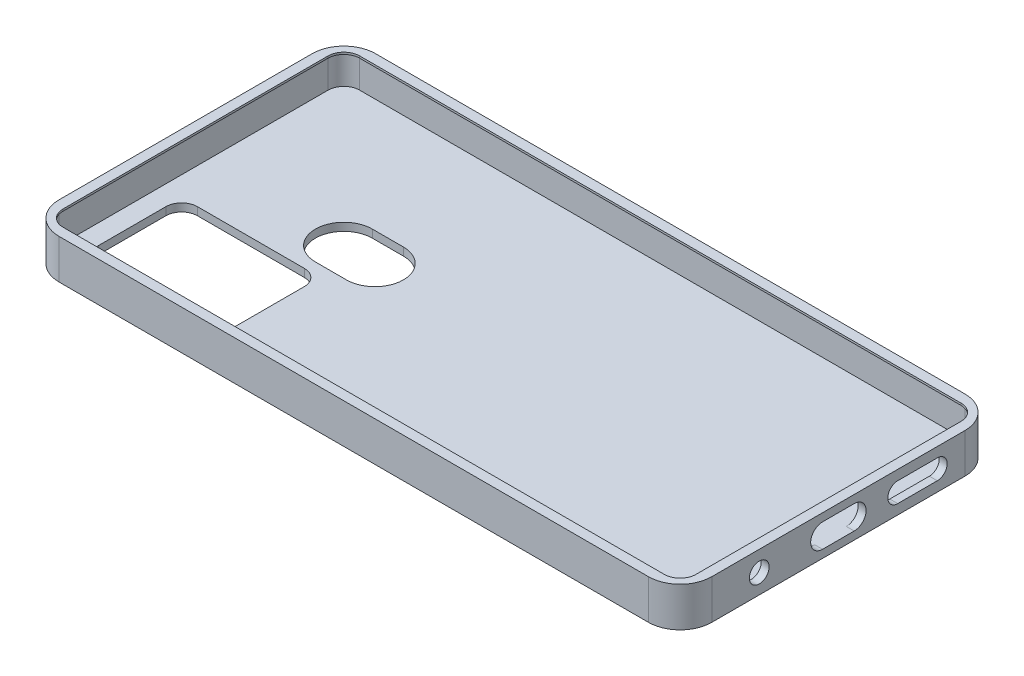
SolidWorks part; units mm, degrees
ref_plane "Front Plane" through (0, 0, 0) normal (0, 0, 1) x (1, 0, 0)
ref_plane "Top Plane" through (0, 0, 0) normal (0, 1, 0) x (1, 0, 0)
ref_plane "Right Plane" through (0, 0, 0) normal (1, 0, 0) x (0, 0, -1)
sketch "Sketch1" plane through (0, 0, 0) normal (0, 1, 0) x (1, 0, 0)
  line L1 (-74.5, 40) -> (74.5, 40)
  line L2 (-82.5, 32) -> (-82.5, -32)
  line L3 (-74.5, -40) -> (74.5, -40)
  line L4 (82.5, 32) -> (82.5, -32)
  arc A0 (74.5, -40) -> (82.5, -32) centre (74.5, -32) ccw
  arc A1 (74.5, 40) -> (82.5, 32) centre (74.5, 32) cw
  arc A2 (-74.5, 40) -> (-82.5, 32) centre (-74.5, 32) ccw
  arc A3 (-82.5, -32) -> (-74.5, -40) centre (-74.5, -32) ccw
  point P7 (82.5, -40)
  point P10 (82.5, 40)
  point P13 (-82.5, 40)
  dimension "D5" = 8
  dimension "D1" = 165
  dimension "D2" = 80
  dimension "D3" = 82.5
  dimension "D4" = 40
extrude "Boss-Extrude1" add sketch "Sketch1" along normal blind 10
sketch "Sketch2" plane through (0, 10, 0) normal (0, 1, 0) x (1, 0, 0)
  line L0 (74.5, 40) -> (-74.5, 40) construction
  line L1 (-76.5, 38) -> (76.5, 38)
  line L2 (-80.5, 34) -> (-80.5, -34)
  line L3 (-76.5, -38) -> (76.5, -38)
  line L4 (80.5, 34) -> (80.5, -34)
  line L5 (-74.5, -40) -> (74.5, -40) construction
  line L6 (82.5, -32) -> (82.5, 32) construction
  line L7 (-82.5, 32) -> (-82.5, -32) construction
  arc A0 (76.5, 38) -> (80.5, 34) centre (76.5, 34) cw
  arc A1 (76.5, -38) -> (80.5, -34) centre (76.5, -34) ccw
  arc A2 (-80.5, -34) -> (-76.5, -38) centre (-76.5, -34) ccw
  arc A3 (-76.5, 38) -> (-80.5, 34) centre (-76.5, 34) ccw
  dimension "D5" = 4
  dimension "D1" = 2
  dimension "D2" = 2
  dimension "D3" = 2
  dimension "D4" = 2
extrude "Cut-Extrude1" cut sketch "Sketch2" against normal blind 8
sketch "Sketch3" plane through (0, 2, 0) normal (0, 1, 0) x (1, 0, 0)
  line L0 (-44.5, 2) -> (-36.6451, 2) construction
  line L1 (-71.5, -8) -> (-44.5, -8)
  line L2 (-75.5, -12) -> (-75.5, -29)
  line L3 (-71.5, -33) -> (-44.5, -33)
  line L4 (-40.5, -12) -> (-40.5, -29)
  line L5 (-76.5, -38) -> (76.5, -38) construction
  line L6 (-80.5, 34) -> (-80.5, -34) construction
  line L7 (-44.5, 9.1985) -> (-36.6451, 9.1985)
  line L8 (-44.5, -5.1985) -> (-36.6451, -5.1985)
  line L9 (-74.5, -40) -> (74.5, -40) construction
  arc A0 (-71.5, -8) -> (-75.5, -12) centre (-71.5, -12) ccw
  arc A1 (-44.5, -8) -> (-40.5, -12) centre (-44.5, -12) cw
  arc A2 (-44.5, -33) -> (-40.5, -29) centre (-44.5, -29) ccw
  arc A3 (-75.5, -29) -> (-71.5, -33) centre (-71.5, -29) ccw
  arc A4 (-44.5, 9.1985) -> (-44.5, -5.1985) centre (-44.5, 2) ccw
  arc A5 (-36.6451, -5.1985) -> (-36.6451, 9.1985) centre (-36.6451, 2) ccw
  point P10 (-75.5, -8)
  point P13 (-40.5, -8)
  point P16 (-40.5, -33)
  point P21 (-40.5726, 2)
  point P26 (0, 0)
  dimension "D5" = 4
  dimension "D1" = 35
  dimension "D2" = 25
  dimension "D3" = 5
  dimension "D4" = 5
  dimension "D6" = 42
extrude "Cut-Extrude2" cut sketch "Sketch3" against normal blind 8
sketch "Sketch4" plane through (82.5, 0, 0) normal (1, 0, 0) x (0, 0, -1)
  line L0 (-4, 5) -> (4, 5) construction
  line L1 (-4, 8) -> (4, 8)
  line L2 (-4, 2) -> (4, 2)
  line L3 (15, 5) -> (25, 5) construction
  line L4 (15, 7.5) -> (25, 7.5)
  line L5 (15, 2.5) -> (25, 2.5)
  arc A0 (-4, 8) -> (-4, 2) centre (-4, 5) ccw
  arc A1 (4, 2) -> (4, 8) centre (4, 5) ccw
  arc A2 (15, 7.5) -> (15, 2.5) centre (15, 5) ccw
  arc A3 (25, 2.5) -> (25, 7.5) centre (25, 5) ccw
  circle A4 centre (-20, 4.9172) radius 2.5
  point P2 (0, 5)
  point P10 (20, 5)
  point P17 (0, 0)
  dimension "D3" = 3
  dimension "D4" = 10
  dimension "D5" = 2.5
  dimension "D6" = 5
  dimension "D1" = 8
  dimension "D2" = 4
  dimension "D7" = 20
  dimension "D8" = 20
  dimension "D9" = 5
extrude "Cut-Extrude3" cut sketch "Sketch4" against normal blind 8
sketch "Sketch6" plane through (0, 10, 0) normal (0, 1, 0) x (1, 0, 0)
  line L0 (76.5, 38) -> (-76.5, 38) construction
  line L1 (-80.5, 34) -> (-80.5, -34) construction
  line L2 (-76.5, -38) -> (76.5, -38) construction
  line L3 (80.5, -34) -> (80.5, 34) construction
  line L4 (80.5, -34) -> (80.5, 34)
  line L5 (-76.5, -38) -> (76.5, -38)
  line L6 (-80.5, 34) -> (-80.5, -34)
  line L7 (76.5, 38) -> (-76.5, 38)
  line L9 (-76, 37.5) -> (76, 37.5)
  line L10 (-80, 33.5) -> (-80, -33.5)
  line L11 (-76, -37.5) -> (76, -37.5)
  line L12 (80, 33.5) -> (80, -33.5)
  arc A0 (80.5, 34) -> (76.5, 38) centre (76.5, 34) ccw construction
  arc A1 (-76.5, 38) -> (-80.5, 34) centre (-76.5, 34) ccw construction
  arc A2 (-80.5, -34) -> (-76.5, -38) centre (-76.5, -34) ccw construction
  arc A3 (76.5, -38) -> (80.5, -34) centre (76.5, -34) ccw construction
  arc A4 (-80, -33.5) -> (-76, -37.5) centre (-76, -33.5) ccw
  arc A5 (80.5, 34) -> (76.5, 38) centre (76.5, 34) ccw
  arc A6 (76.5, -38) -> (80.5, -34) centre (76.5, -34) ccw
  arc A7 (-80.5, -34) -> (-76.5, -38) centre (-76.5, -34) ccw
  arc A8 (-76.5, 38) -> (-80.5, 34) centre (-76.5, 34) ccw
  arc A9 (76, -37.5) -> (80, -33.5) centre (76, -33.5) ccw
  arc A10 (76, 37.5) -> (80, 33.5) centre (76, 33.5) cw
  arc A11 (-76, 37.5) -> (-80, 33.5) centre (-76, 33.5) ccw
  point P3 (79.3284, 36.8284)
  dimension "D5" = 4
  dimension "D1" = 0.5
  dimension "D2" = 0.5
  dimension "D3" = 0.5
  dimension "D4" = 0.5
extrude "Boss-Extrude2" add sketch "Sketch6" against normal blind 0.5
